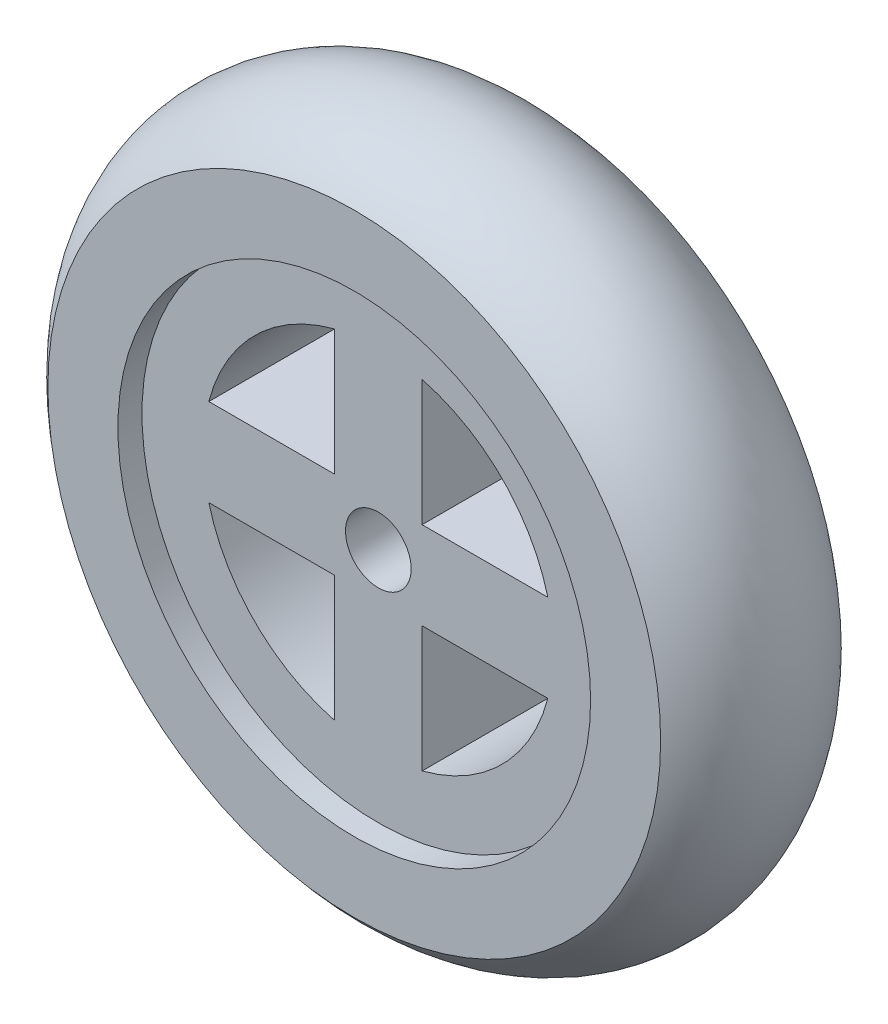
SolidWorks part; units mm, degrees
material "Rubber"
ref_plane "Front Plane" through (0, 0, 0) normal (0, 0, 1) x (1, 0, 0)
ref_plane "Top Plane" through (0, 0, 0) normal (0, 1, 0) x (1, 0, 0)
ref_plane "Right Plane" through (0, 0, 0) normal (1, 0, 0) x (0, 0, -1)
sketch "Sketch1" plane through (0, 0, 0) normal (0, 1, 0) x (1, 0, 0)
  line L0 (0, -7131.7252) -> (0, 349454.537) construction
  line L1 (40, 0) -> (0, 0) construction
  line L2 (40, 15) -> (40, -15)
  line L3 (40, 15) -> (54, 15)
  line L4 (54, 15) -> (54, 20.5)
  line L5 (54, 20.5) -> (70, 20.5)
  line L6 (70, -20.5) -> (54, -20.5)
  line L7 (54, -20.5) -> (54, -15)
  line L8 (54, -15) -> (40, -15)
  arc A2 (70, 20.5) -> (70, -20.5) centre (54.0078, 0) cw
  dimension "D5" = 40
  dimension "D2" = 16
  dimension "D1" = 30
  dimension "D6" = 26
  dimension "D3" = 5.5
  dimension "D4" = 14
revolve "Revolve1" add sketch "Sketch1" angle 360 about L0
sketch "Sketch3" plane through (0, 0, 0) normal (0, 1, 0) x (1, 0, 0)
  line L0 (-1000, 0) -> (49000, 0) construction
  line L2 (-40, 15) -> (40, 15)
  line L3 (-40, 15) -> (-40, -15)
  line L4 (-40, -15) -> (40, -15)
  line L5 (40, 15) -> (40, -15)
  line L6 (-40, 15) -> (40, -15) construction
  line L7 (-40, -15) -> (40, 15) construction
  point P1 (0, 0)
  dimension "D1" = 80
  dimension "D2" = 30
extrude "Boss-Extrude3" add sketch "Sketch3" along normal mid plane 20 contours L3 L2 L5 L4
sketch "Sketch5" plane through (0, 0, 0) normal (1, 0, 0) x (0, 0, -1)
  line L1 (-15, 40) -> (15, 40)
  line L2 (-15, 40) -> (-15, -40)
  line L3 (-15, -40) -> (15, -40)
  line L4 (15, 40) -> (15, -40)
  line L5 (-15, 40) -> (15, -40) construction
  line L6 (-15, -40) -> (15, 40) construction
  point P0 (0, 0)
  dimension "D1" = 80
  dimension "D2" = 30
extrude "Boss-Extrude4" add sketch "Sketch5" along normal mid plane 20
sketch "Sketch7" plane through (0, 0, 0) normal (0, 0, 1) x (1, 0, 0)
  circle A0 centre (0, 0) radius 7.5
  dimension "D1" = 15
extrude "Cut-Extrude1" cut sketch "Sketch7" against normal through all both and the other way through all
